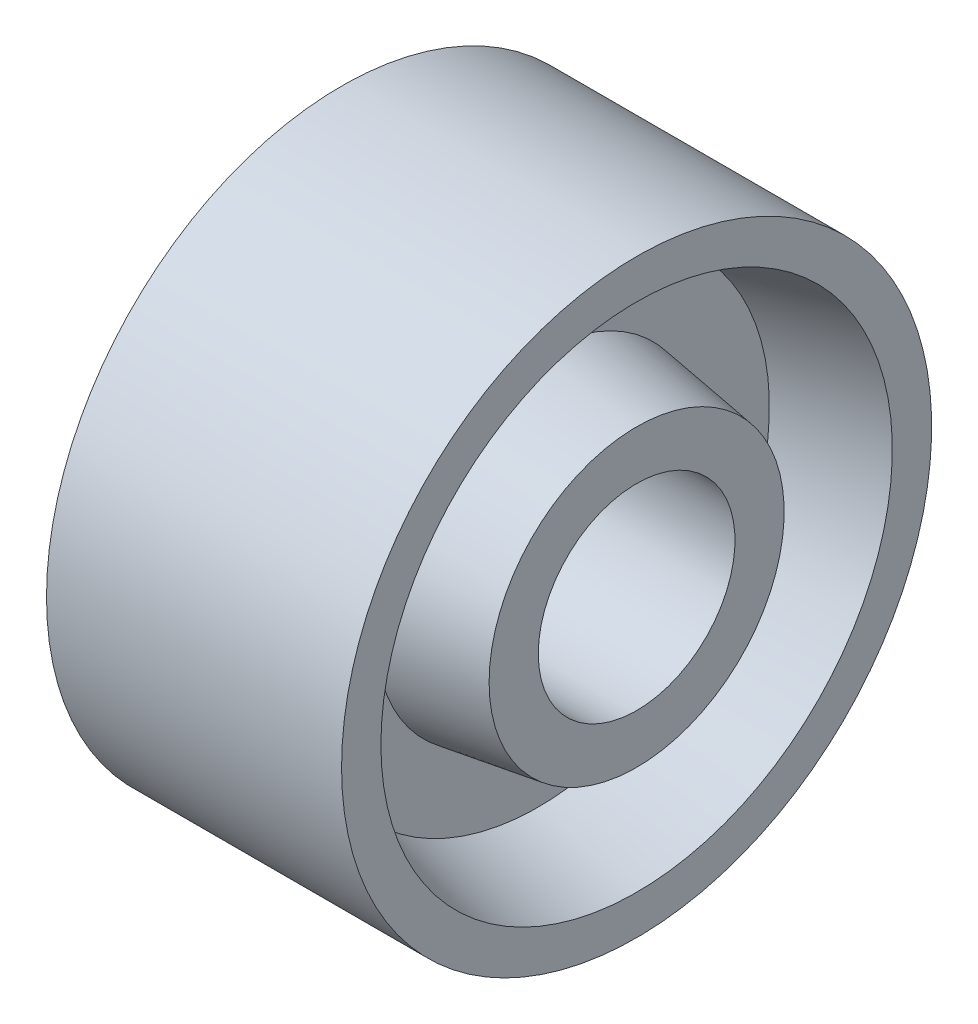
SolidWorks part; units mm, degrees
ref_plane "Ön Düzlem" through (0, 0, 0) normal (0, 0, 1) x (1, 0, 0)
ref_plane "Üst Düzlem" through (0, 0, 0) normal (0, 1, 0) x (1, 0, 0)
ref_plane "Sağ Düzlem" through (0, 0, 0) normal (1, 0, 0) x (0, 0, -1)
sketch "Sketch1" plane through (0, 0, 0) normal (0, 0, 1) x (1, 0, 0)
  line L0 (0, 0) -> (30, 0) construction
  line L1 (0, 10) -> (30, 10)
  line L2 (0, 10) -> (0, 15)
  line L3 (0, 15) -> (10, 16.5)
  line L4 (10, 16.5) -> (10, 23.5)
  line L5 (10, 23.5) -> (0, 26)
  line L6 (0, 26) -> (0, 30)
  line L7 (0, 30) -> (30, 30)
  line L8 (15, 30) -> (15, 10) construction
  line L9 (30, 26) -> (30, 30)
  line L10 (20, 23.5) -> (30, 26)
  line L11 (20, 16.5) -> (20, 23.5)
  line L12 (30, 15) -> (20, 16.5)
  line L13 (30, 10) -> (30, 15)
  point P5 (10, 20)
  dimension "D1" = 30
  dimension "D2" = 10
  dimension "D3" = 15
  dimension "D4" = 15
  dimension "D5" = 26
  dimension "D6" = 30
  dimension "D7" = 7
  dimension "D8" = 10
  dimension "D9" = 5
revolve "Revolve1" add sketch "Sketch1" angle 360 about L0
